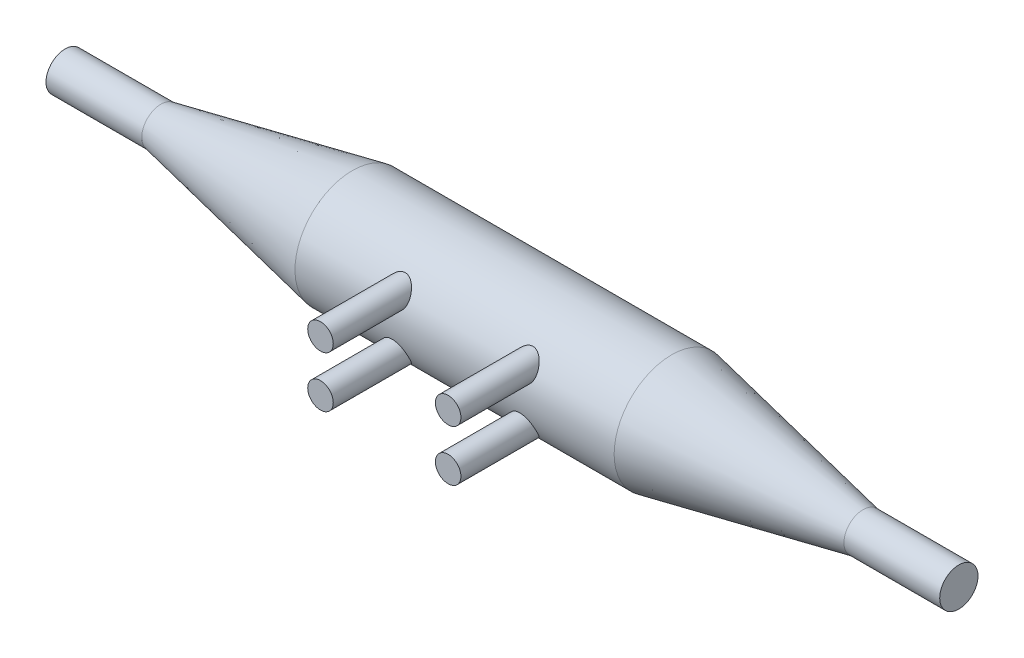
SolidWorks part; units mm, degrees
ref_plane "Front Plane" through (0, 0, 0) normal (0, 0, 1) x (1, 0, 0)
ref_plane "Top Plane" through (0, 0, 0) normal (0, 1, 0) x (1, 0, 0)
ref_plane "Right Plane" through (0, 0, 0) normal (1, 0, 0) x (0, 0, -1)
sketch "Sketch1" plane through (0, 0, 0) normal (0, 0, 1) x (1, 0, 0)
  line L0 (-16.7408, 3) -> (-1.7408, 3)
  line L1 (-1.7408, 3) -> (28.2592, 9)
  line L2 (28.2592, 9) -> (78.2592, 9)
  line L3 (78.2592, 9) -> (108.2592, 3)
  line L4 (108.2592, 3) -> (123.2592, 3)
  line L5 (123.2592, 3) -> (123.2592, 0)
  line L6 (123.2592, 0) -> (-16.7408, 0)
  line L7 (-16.7408, 0) -> (-16.7408, 3)
  dimension "D1" = 3
  dimension "D2" = 9
  dimension "D3" = 30
  dimension "D4" = 140
  dimension "D5" = 30
  dimension "D6" = 15
  dimension "D7" = 15
revolve "Revolve1" add sketch "Sketch1" angle 360 about L6
sketch "Sketch2" plane through (0, 0, 0) normal (0, 0, 1) x (1, 0, 0)
  line L0 (21.8042, 4) -> (64.597, 4) construction
  line L1 (21.8042, -4) -> (64.597, -4) construction
  line L2 (78.2592, 9) -> (28.2592, 9) construction
  line L3 (43.2592, 4) -> (43.2592, -4) construction
  line L4 (28.2592, 9) -> (28.2592, -9) construction
  circle A0 centre (43.2592, 4) radius 2
  circle A1 centre (43.2592, -4) radius 2
  circle A2 centre (63.2592, 4) radius 2
  circle A3 centre (63.2592, -4) radius 2
  dimension "D5" = 15
  dimension "D1" = 8
  dimension "D2" = 5
  dimension "D3" = 20
  dimension "D4" = 20
extrude "Boss-Extrude1" add sketch "Sketch2" along normal blind 20
